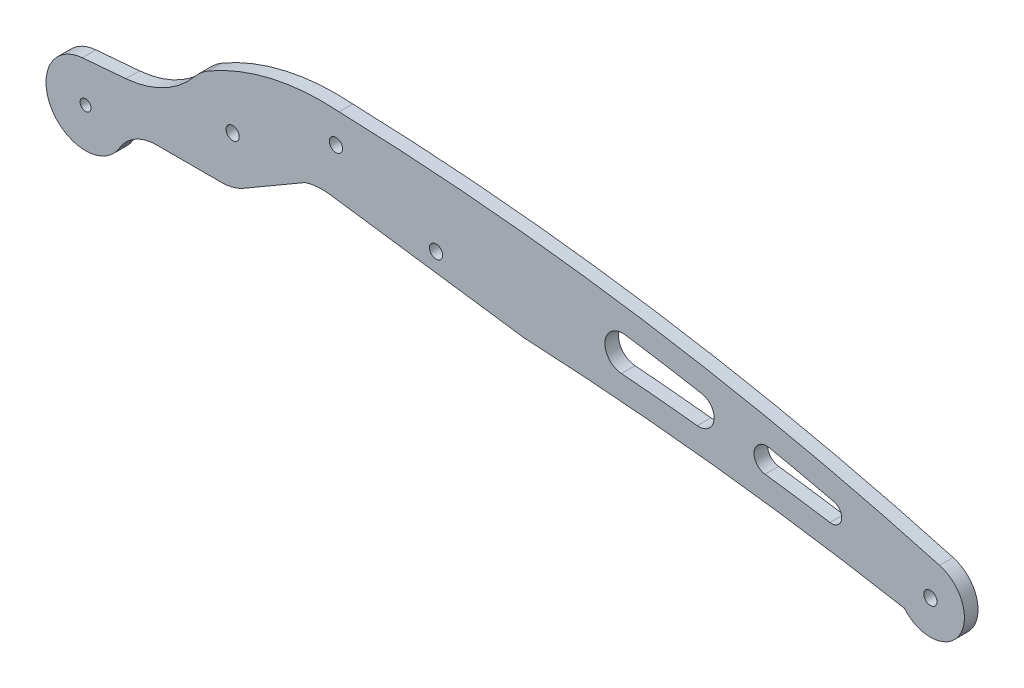
SolidWorks part; units mm, degrees
ref_plane "Front Plane" through (0, 0, 0) normal (0, 0, 1) x (1, 0, 0)
ref_plane "Top Plane" through (0, 0, 0) normal (0, 1, 0) x (1, 0, 0)
ref_plane "Right Plane" through (0, 0, 0) normal (1, 0, 0) x (0, 0, -1)
sketch "Sketch1" plane through (0, 0, 0) normal (0, 0, 1) x (1, 0, 0)
  line L0 (85.6, -33.2) -> (-2.7185, -20.8785)
  line L1 (-14, -21.8) -> (-42.0398, -38.0927)
  line L2 (-52.0878, -40.8) -> (-81.6991, -40.8)
  line L4 (-115.5, -23.3126) -> (-95.6181, -21.65)
  line L9 (86.6343, -22.2378) -> (-1.1986, -9.984) construction
  line L10 (-18.5488, -11.7209) -> (-47.5662, -28.5817) construction
  line L11 (-52.0878, -29.8) -> (-81.6991, -29.8) construction
  line L12 (-114.5833, -34.2743) -> (-94.7014, -32.6117) construction
  circle A0 centre (-114, -41.25) radius 2.5
  circle A1 centre (270.7, -43.25) radius 2.5
  circle A2 centre (-47, -18.8) radius 3
  circle A3 centre (45.6, -19.2) radius 3
  circle A4 centre (0, 0) radius 3
  circle A5 centre (-114, -41.25) radius 4 construction
  circle A6 centre (270.7, -43.25) radius 3
  arc A15 (258.8573, -53.25) -> (85.6, -33.2) centre (20.2413, -1356.587) ccw
  arc A16 (-2.7185, -20.8785) -> (-14, -21.8) centre (-6.3, -46.55) ccw
  arc A17 (-81.6991, -40.8) -> (-98.4956, -50.394) centre (-81.6991, -60.3) ccw
  arc A18 (-115.5, -23.3126) -> (-98.4956, -50.394) centre (-114, -41.25) ccw
  arc A20 (-95.6181, -21.65) -> (-64.3414, -5.2) centre (-99.3924, 23.4848) ccw
  arc A21 (1.5, 13.8188) -> (-58, 0.2) centre (-6.3009, -88.8853) ccw
  arc A22 (274.8783, -28.3238) -> (1.5, 13.8188) centre (-36.5716, -1140.9217) ccw
  arc A23 (258.8573, -53.25) -> (274.8783, -28.3238) centre (270.7, -43.25) ccw
  arc A24 (-42.0398, -38.0927) -> (-52.0878, -40.8) centre (-52.0878, -20.8) cw
  arc A25 (-64.3414, -5.2) -> (-58, 0.2) centre (-46.2959, -19.9679) cw
  arc A26 (226.7442, -27.2598) -> (197.0716, -20.6588) centre (-36.5716, -1140.9217) ccw
  arc A34 (224.9645, -36.3657) -> (195.4065, -32.1199) centre (20.2413, -1356.587) ccw
  arc A36 (132.3472, -9.0893) -> (130.0105, -25.1041) centre (130.6, -17.0123) ccw
  arc A37 (166.5349, -14.722) -> (164.5602, -28.4048) centre (165.3074, -21.5287) cw
  arc A38 (197.0716, -20.6588) -> (195.4065, -32.1199) centre (196.1658, -26.3787) ccw
  arc A39 (226.7442, -27.2598) -> (224.9645, -36.3657) centre (225.676, -31.7779) cw
  arc A40 (271.9131, -38.9166) -> (0.8958, 2.8327) centre (-36.5716, -1140.9217) ccw construction
  arc A41 (266.2033, -43.4234) -> (86.6343, -22.2378) centre (20.2413, -1356.587) ccw construction
  arc A42 (266.2033, -43.4234) -> (271.9131, -38.9166) centre (270.7, -43.25) ccw construction
  arc A43 (166.5349, -14.722) -> (132.3472, -9.0893) centre (-36.5716, -1140.9217) ccw
  arc A44 (164.5602, -28.4048) -> (130.0105, -25.1041) centre (20.2413, -1356.587) ccw
  arc A46 (-1.1986, -9.984) -> (-18.5488, -11.7209) centre (-6.3, -46.55) ccw construction
  arc A47 (-47.5662, -28.5817) -> (-52.0878, -29.8) centre (-52.0878, -20.8) cw construction
  arc A48 (0.8958, 2.8327) -> (-52.4787, -9.314) centre (-6.3009, -88.8853) ccw construction
  arc A49 (-94.7014, -32.6117) -> (-55.8286, -12.1666) centre (-99.3924, 23.4848) ccw construction
  arc A50 (-55.8286, -12.1666) -> (-52.4787, -9.314) centre (-46.2959, -19.9679) cw construction
  arc A51 (-81.6991, -29.8) -> (-107.9705, -44.806) centre (-81.6991, -60.3) ccw construction
  arc A52 (-114.5833, -34.2743) -> (-107.9705, -44.806) centre (-114, -41.25) ccw construction
  point P52 (-46.6991, -40.8)
  dimension "D1" = 6
  dimension "D6" = 67
  dimension "D7" = 22.45
  dimension "D8" = 18
  dimension "D9" = 103
  dimension "D14" = 19.5
  dimension "D17" = 20
  dimension "D22" = 5
  dimension "D23" = 15.5
  dimension "D24" = 1325
  dimension "D36" = 8.1133
  dimension "D37" = 2.1877
  dimension "D41" = 11
  dimension "D42" = 5
  dimension "D35" = 35
  dimension "D2" = 18.8
  dimension "D3" = 47
  dimension "D4" = 45.6
  dimension "D5" = 19.2
  dimension "D10" = 46.55
  dimension "D11" = 6.3
  dimension "D12" = 35
  dimension "D13" = 22
  dimension "D15" = 33
  dimension "D16" = 3
  dimension "D18" = 40
  dimension "D19" = 14
  dimension "D20" = 270.7
  dimension "D21" = 43.25
  dimension "D25" = 10
  dimension "D26" = 14.9262
  dimension "D27" = 13.9
  dimension "D28" = 1.5
  dimension "D29" = 11
  dimension "D30" = 19
  dimension "D31" = 1.5
  dimension "D32" = 19.6
  dimension "D33" = 13.6
  dimension "D34" = 85
  dimension "D38" = 30.8584
  dimension "D39" = 4.85
  dimension "D40" = 30
extrude "Boss-Extrude1" add sketch "Sketch1" along normal blind 6.2
